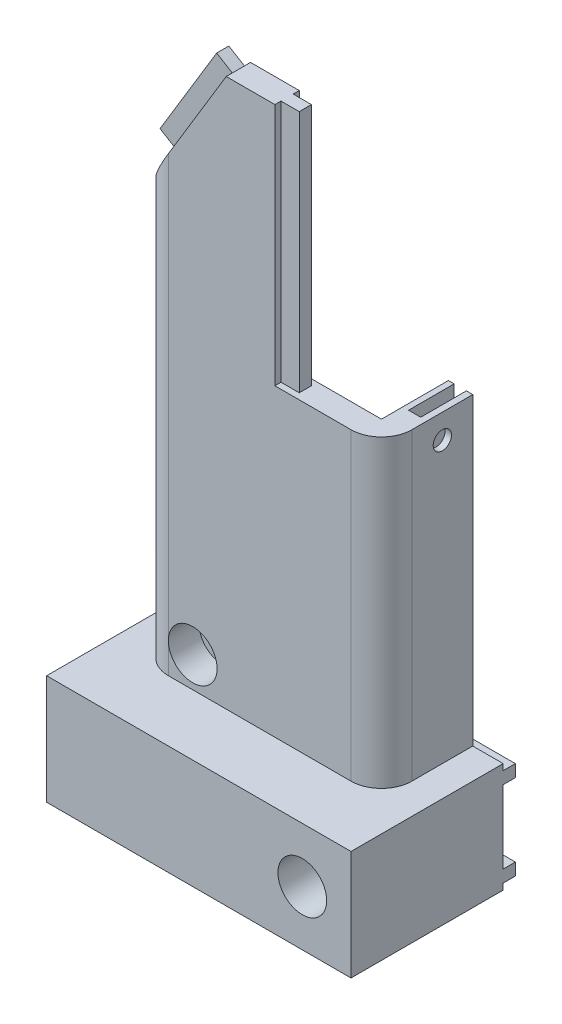
SolidWorks part; units mm, degrees
ref_plane "Front Plane" through (0, 0, 0) normal (0, 0, 1) x (1, 0, 0)
ref_plane "Top Plane" through (0, 0, 0) normal (0, 1, 0) x (1, 0, 0)
ref_plane "Right Plane" through (0, 0, 0) normal (1, 0, 0) x (0, 0, -1)
sketch "Sketch1" plane through (0, 0, 0) normal (0, 1, 0) x (1, 0, 0)
  line L1 (-20, -15) -> (20, -15)
  line L2 (-20, -15) -> (-20, 15)
  line L3 (-20, 15) -> (20, 15)
  line L4 (20, -15) -> (20, 15)
  line L5 (-20, -15) -> (20, 15) construction
  line L6 (-20, 15) -> (20, -15) construction
  point P0 (0, 0)
  dimension "D1" = 40
  dimension "D2" = 30
extrude "Boss-Extrude1" add sketch "Sketch1" along normal blind 90
shell "Shell1" thickness 4
fillet "Fillet1" radius 5 4 edges at (20, 45, -15) (20, 45, 15) (-20, 45, -15) (-20, 45, 15)
sketch "Sketch2" plane through (0, 0, 0) normal (0, 0, 1) x (1, 0, 0)
  line L0 (-5.5, 90) -> (-20, 66)
  line L1 (16, 90) -> (-16, 90) construction
  line L2 (-20, 90) -> (-20, 0) construction
  line L3 (-20, 66) -> (-20, 90)
  line L4 (-20, 90) -> (-5.5, 90)
  dimension "D1" = 5.5
  dimension "D2" = 66
extrude "Cut-Extrude1" cut sketch "Sketch2" against normal through all both and the other way through all
sketch "Sketch3" plane through (0, 0, 0) normal (0, 0, 1) x (1, 0, 0)
  line L1 (20, 90) -> (2.5, 90)
  line L2 (20, 90) -> (20, 50)
  line L3 (20, 50) -> (2.5, 50)
  line L4 (2.5, 90) -> (2.5, 50)
  dimension "D1" = 40
  dimension "D2" = 17.5
extrude "Cut-Extrude2" cut sketch "Sketch3" against normal through all both and the other way through all
sketch "Sketch5" plane through (2.5, 0, 0) normal (1, 0, 0) x (0, 0, -1)
  line L0 (-13, 90) -> (-13, 50) construction
  line L1 (-11, 90) -> (-15, 90) construction
  line L2 (-11, 50) -> (-15, 50) construction
  line L4 (-14, 90) -> (-12, 90)
  line L5 (-14, 90) -> (-14, 50)
  line L6 (-14, 50) -> (-12, 50)
  line L7 (-12, 90) -> (-12, 50)
  dimension "D1" = 2
extrude "Boss-Extrude2" add sketch "Sketch5" along normal blind 3
mirror "Mirror1" about plane through (0, 0, 0) normal (0, 0, 1) of "Boss-Extrude2"
sketch "Sketch6" plane through (-43.8639, 26.5011, 0) normal (-0.8559, 0.5171, 0) x (0, 0, 1)
  line L0 (-13, 74.1883) -> (-13, 56.1883) construction
  line L1 (-15, 74.1883) -> (-11, 74.1883) construction
  line L3 (-14, 74.1883) -> (-12, 74.1883)
  line L4 (-14, 74.1883) -> (-14, 56.1883)
  line L5 (-14, 56.1883) -> (-12, 56.1883)
  line L6 (-12, 74.1883) -> (-12, 56.1883)
  dimension "D1" = 18
  dimension "D2" = 2
extrude "Boss-Extrude3" add sketch "Sketch6" along normal blind 3
mirror "Mirror2" about plane through (0, 0, 0) normal (0, 0, 1) of "Boss-Extrude3"
sketch "Sketch8" plane through (0, 0, 0) normal (0, 1, 0) x (1, 0, 0)
  line L1 (-25, -25) -> (25, -25)
  line L2 (-25, -25) -> (-25, 25)
  line L3 (-25, 25) -> (25, 25)
  line L4 (25, -25) -> (25, 25)
  line L5 (-25, -25) -> (25, 25) construction
  line L6 (-25, 25) -> (25, -25) construction
  point P0 (0, 0)
  dimension "D1" = 50
  dimension "D2" = 50
extrude "Boss-Extrude4" add sketch "Sketch8" against normal blind 18
sketch "Sketch10" plane through (-25, 0, 0) normal (-1, 0, 0) x (0, 0, 1)
  line L0 (-25, -9) -> (25, -9) construction
  line L1 (-22.5, -14) -> (22.5, -14)
  line L2 (-22.5, -14) -> (-22.5, -4)
  line L3 (-22.5, -4) -> (22.5, -4)
  line L4 (22.5, -14) -> (22.5, -4)
  line L5 (-22.5, -14) -> (22.5, -4) construction
  line L6 (-22.5, -4) -> (22.5, -14) construction
  line L7 (-25, -18) -> (-25, 0) construction
  line L8 (25, -18) -> (25, 0) construction
  line L9 (0, 0) -> (0, -18) construction
  line L10 (-25, -18) -> (25, -18) construction
  point P0 (0, -9)
  dimension "D1" = 45
  dimension "D2" = 10
extrude "Cut-Extrude4" cut sketch "Sketch10" against normal blind 37.5
sketch "Sketch15" plane through (0, 0, -11) normal (0, 0, 1) x (1, 0, 0)
  line L1 (-16, 0) -> (-6, 0)
  line L2 (-16, 0) -> (-16, 10)
  line L3 (-16, 10) -> (-6, 10)
  line L4 (-6, 0) -> (-6, 10)
  dimension "D1" = 10
  dimension "D2" = 10
extrude "Boss-Extrude5" add sketch "Sketch15" along normal up to next
sketch "Sketch20" plane through (0, 0, -15) normal (0, 0, -1) x (-1, 0, 0)
  line L0 (16, 72.6207) -> (16, 10) construction
  line L2 (-16, 0) -> (6, 0) construction
  circle A0 centre (11, 5) radius 2
  dimension "D2" = 5
  dimension "D3" = 4
  dimension "D1" = 5
extrude "Cut-Extrude8" cut sketch "Sketch20" against normal through all both and the other way through all
sketch "Sketch21" plane through (0, 0, -15) normal (0, 0, -1) x (-1, 0, 0)
  circle A0 centre (11, 5) radius 4
  dimension "D1" = 8
extrude "Cut-Extrude9" cut sketch "Sketch21" against normal blind 5
mirror "Mirror3" about plane through (0, 0, 0) normal (0, 0, 1) of "Cut-Extrude9"
sketch "Sketch23" plane through (0, 50, 0) normal (0, 1, 0) x (1, 0, 0)
  line L0 (0, 0) -> (20, 0) construction
  line L1 (16.9495, 7.5) -> (18.9495, 7.5)
  line L2 (16.9495, 7.5) -> (16.9495, -7.5)
  line L3 (16.9495, -7.5) -> (18.9495, -7.5)
  line L4 (18.9495, 7.5) -> (18.9495, -7.5)
  line L5 (20, 10) -> (20, -10) construction
  line L6 (16, 11) -> (19.899, 11) construction
  line L7 (16, -11) -> (19.899, -11) construction
  line L8 (17.9495, 11) -> (17.9495, -11) construction
  arc A0 (20, 10) -> (15, 15) centre (15, 10) ccw construction
  arc A1 (15, -15) -> (20, -10) centre (15, -10) ccw construction
  dimension "D1" = 2
  dimension "D2" = 15
extrude "Cut-Extrude10" cut sketch "Sketch23" against normal blind 10
sketch "Sketch24" plane through (20, 0, 0) normal (1, 0, 0) x (0, 0, -1)
  line L0 (-10, 50) -> (-10, 0) construction
  line L1 (10, 50) -> (-10, 50) construction
  circle A0 centre (-5, 46) radius 1.5
  dimension "D3" = 3
  dimension "D1" = 5
  dimension "D2" = 4
extrude "Cut-Extrude11" cut sketch "Sketch24" against normal blind 10 and the other way through all
mirror "Mirror4" about plane through (0, 0, 0) normal (0, 0, 1) of "Cut-Extrude11"
sketch "Sketch27" plane through (0, 0, 0) normal (0, 1, 0) x (1, 0, 0)
  line L0 (25, -25) -> (25, 25) construction
  line L1 (-25, 25) -> (25, 25)
  line L2 (-25, 25) -> (-25, 0)
  line L3 (-25, 0) -> (25, 0)
  line L4 (25, 25) -> (25, 0)
extrude "Cut-Extrude12" cut sketch "Sketch27" against normal through all both and the other way through all
sketch "Sketch29" plane through (0, 0, 0) normal (0, 0, -1) x (-1, 0, 0)
  line L0 (25, -2) -> (-25, -2) construction
  line L1 (25, -4) -> (25, 0) construction
  line L2 (-25, -18) -> (-25, 0) construction
  line L3 (25, -1) -> (-25, -1)
  line L4 (25, -1) -> (25, -3)
  line L5 (25, -3) -> (-25, -3)
  line L6 (-25, -1) -> (-25, -3)
  dimension "D1" = 2
extrude "Boss-Extrude6" add sketch "Sketch29" along normal blind 2
sketch "Sketch30" plane through (0, 0, 0) normal (0, 0, -1) x (-1, 0, 0)
  line L0 (25, -16) -> (-25, -16) construction
  line L1 (25, -18) -> (25, -14) construction
  line L2 (-25, -18) -> (-25, -3) construction
  line L4 (-25, -15) -> (25, -15)
  line L5 (-25, -15) -> (-25, -17)
  line L6 (-25, -17) -> (25, -17)
  line L7 (25, -15) -> (25, -17)
  dimension "D1" = 2
extrude "Boss-Extrude7" add sketch "Sketch30" along normal blind 2
sketch "Sketch31" plane through (0, 0, 25) normal (0, 0, 1) x (1, 0, 0)
  line L0 (25, -18) -> (25, 0) construction
  line L1 (-25, -18) -> (25, -18) construction
  circle A0 centre (17, -9) radius 2
  dimension "D1" = 4
  dimension "D2" = 8
  dimension "D3" = 9
extrude "Cut-Extrude13" cut sketch "Sketch31" against normal through all both and the other way through all
sketch "Sketch32" plane through (0, 0, 25) normal (0, 0, 1) x (1, 0, 0)
  circle A0 centre (17, -9) radius 4
  dimension "D1" = 8
extrude "Cut-Extrude14" cut sketch "Sketch32" against normal blind 15
